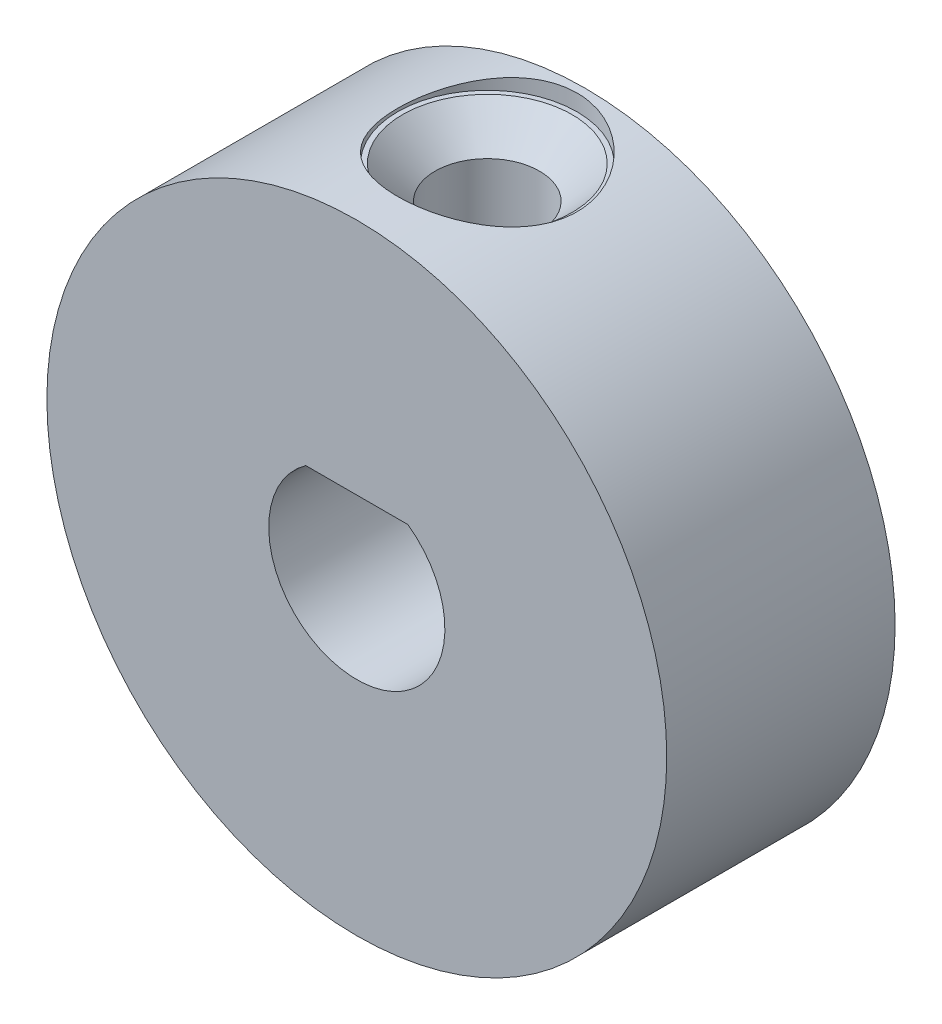
SolidWorks part; units mm, degrees
ref_plane "Plan de face" through (0, 0, 0) normal (0, 0, 1) x (1, 0, 0)
ref_plane "Plan de dessus" through (0, 0, 0) normal (0, 1, 0) x (1, 0, 0)
ref_plane "Plan de droite" through (0, 0, 0) normal (1, 0, 0) x (0, 0, -1)
sketch "Esquisse1" plane through (0, 0, 0) normal (0, 0, 1) x (1, 0, 0)
  line L0 (-1.5, 2) -> (1.5, 2) construction
  line L1 (-1.5652, 2.2) -> (1.5652, 2.2)
  arc A0 (-1.5, 2) -> (1.5, 2) centre (0, 0) ccw construction
  circle A2 centre (0, 0) radius 9.5
  arc A3 (-1.5652, 2.2) -> (1.5652, 2.2) centre (0, 0) ccw
  point P1 (0, 0)
  point P7 (0, 0)
  dimension "D1" = 2.5
  dimension "D2" = 2
  dimension "D3" = 0.2
  dimension "D4" = 19
extrude "Boss.-Extru.1" add sketch "Esquisse1" along normal blind 7
sketch "Esquisse2" plane through (0, 0, 0) normal (0, 0, -1) x (-1, 0, 0)
  line L0 (1.5652, 2.2) -> (-1.5652, 2.2) construction
  line L1 (-2.75, 3.2) -> (2.75, 3.2)
  line L2 (-2.75, 3.2) -> (-2.75, 5.4)
  line L3 (-2.75, 5.4) -> (2.75, 5.4)
  line L4 (2.75, 3.2) -> (2.75, 5.4)
  line L5 (-2.75, 3.2) -> (2.75, 5.4) construction
  line L6 (-2.75, 5.4) -> (2.75, 3.2) construction
  point P0 (0, 4.3)
  point P14 (0, 0)
  point P15 (0, 0)
  dimension "D1" = 2.2
  dimension "D2" = 5.5
  dimension "D3" = 1
extrude "Enlèv. mat.-Extru.1" cut sketch "Esquisse2" against normal blind 6
sketch "Esquisse3" plane through (0, 3.2, 0) normal (0, 1, 0) x (1, 0, 0)
  circle A0 centre (0, -3) radius 1.6
  dimension "D1" = 3.2
  dimension "D2" = 3
extrude "Enlèv. mat.-Extru.2" cut sketch "Esquisse3" against normal up to next and the other way up to next
ref_plane "Plan2" through (0, 9, 0) normal (0, 1, 0) x (1, 0, 0)
sketch "Esquisse7" plane through (0, 9, 0) normal (0, 1, 0) x (1, 0, 0)
  circle A0 centre (0, -3) radius 2.75
  dimension "D1" = 5.5
extrude "Enlèv. mat.-Extru.4" cut sketch "Esquisse7" along normal through all
chamfer "Chanfrein2" distance 1 angle 45 1 edges at (0, 9, 4.6)
